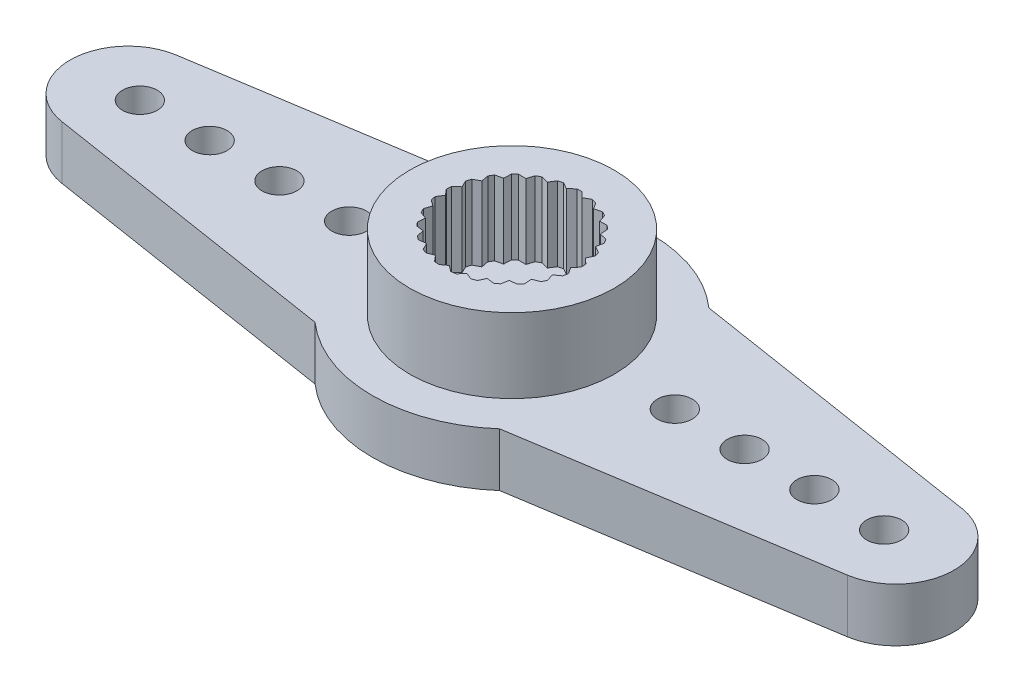
SolidWorks part; units mm, degrees
material "ABS"
ref_plane "Front Plane" through (0, 0, 0) normal (0, 0, 1) x (1, 0, 0)
ref_plane "Top Plane" through (0, 0, 0) normal (0, 1, 0) x (1, 0, 0)
ref_plane "Right Plane" through (0, 0, 0) normal (1, 0, 0) x (0, 0, -1)
sketch "Sketch2" plane through (0, 0, 0) normal (0, 1, 0) x (1, 0, 0)
  circle A0 centre (0, 0) radius 6
  circle A1 centre (0, 0) radius 1.5
  dimension "D1" = 12
  dimension "D2" = 3
extrude "Boss-Extrude1" add sketch "Sketch2" along normal mid plane 2.3
sketch "Sketch3" plane through (0, 1.15, 0) normal (0, 1, 0) x (1, 0, 0)
  line L0 (0, 0) -> (0, 2.9) construction
  line L3 (0, 0) -> (0.376, 2.9763) construction
  line L52 (0.1074, 2.898) -> (0.3384, 2.6787)
  line L53 (-0.1074, 2.898) -> (-0.3384, 2.6787)
  line L54 (0.8248, 2.7802) -> (0.9939, 2.5104)
  line L55 (0.6167, 2.8337) -> (0.3384, 2.6787)
  line L56 (1.4903, 2.4878) -> (1.587, 2.1843)
  line L57 (1.302, 2.5913) -> (0.9939, 2.5104)
  line L58 (2.0621, 2.039) -> (2.0804, 1.721)
  line L59 (1.9055, 2.1861) -> (1.587, 2.1843)
  line L60 (2.5044, 1.4621) -> (2.443, 1.1496)
  line L61 (2.3893, 1.6435) -> (2.0804, 1.721)
  line L62 (2.7894, 0.7934) -> (2.6522, 0.5059)
  line L63 (2.723, 0.9977) -> (2.443, 1.1496)
  line L64 (2.899, 0.0748) -> (2.6947, -0.1695)
  line L65 (2.8855, 0.2892) -> (2.6522, 0.5059)
  line L66 (2.8265, -0.6486) -> (2.5679, -0.8343)
  line L67 (2.8668, -0.4375) -> (2.6947, -0.1695)
  line L68 (2.5765, -1.3311) -> (2.2797, -1.4467)
  line L69 (2.6679, -1.1367) -> (2.5679, -0.8343)
  line L70 (2.1645, -1.93) -> (1.8483, -1.9682)
  line L71 (2.3014, -1.7645) -> (2.2797, -1.4467)
  line L72 (1.6165, -2.4077) -> (1.3007, -2.366)
  line L73 (1.7903, -2.2814) -> (1.8483, -1.9682)
  line L74 (0.967, -2.734) -> (0.6715, -2.6152)
  line L75 (1.1667, -2.655) -> (1.3007, -2.366)
  line L76 (0.2566, -2.8886) -> (0, -2.7)
  line L77 (0.4698, -2.8617) -> (0.6715, -2.6152)
  line L78 (-0.4698, -2.8617) -> (-0.6715, -2.6152)
  line L79 (-0.2566, -2.8886) -> (0, -2.7)
  line L80 (-1.1667, -2.655) -> (-1.3007, -2.366)
  line L81 (-0.967, -2.734) -> (-0.6715, -2.6152)
  line L82 (-1.7903, -2.2814) -> (-1.8483, -1.9682)
  line L83 (-1.6165, -2.4077) -> (-1.3007, -2.366)
  line L84 (-2.3014, -1.7645) -> (-2.2797, -1.4467)
  line L85 (-2.1645, -1.93) -> (-1.8483, -1.9682)
  line L86 (-2.6679, -1.1367) -> (-2.5679, -0.8343)
  line L87 (-2.5765, -1.3311) -> (-2.2797, -1.4467)
  line L88 (-2.8668, -0.4375) -> (-2.6947, -0.1695)
  line L89 (-2.8265, -0.6486) -> (-2.5679, -0.8343)
  line L90 (-2.8855, 0.2892) -> (-2.6522, 0.5059)
  line L91 (-2.899, 0.0748) -> (-2.6947, -0.1695)
  line L92 (-2.723, 0.9977) -> (-2.443, 1.1496)
  line L93 (-2.7894, 0.7934) -> (-2.6522, 0.5059)
  line L94 (-2.3893, 1.6435) -> (-2.0804, 1.721)
  line L95 (-2.5044, 1.4621) -> (-2.443, 1.1496)
  line L96 (-1.9055, 2.1861) -> (-1.587, 2.1843)
  line L97 (-2.0621, 2.039) -> (-2.0804, 1.721)
  line L98 (-1.302, 2.5913) -> (-0.9939, 2.5104)
  line L99 (-1.4903, 2.4878) -> (-1.587, 2.1843)
  line L100 (-0.6167, 2.8337) -> (-0.3384, 2.6787)
  line L101 (-0.8248, 2.7802) -> (-0.9939, 2.5104)
  line L102 (-2.533, 1.6075) -> (-2.3893, 1.6435) construction
  line L103 (-2.533, 1.6075) -> (-2.5044, 1.4621) construction
  line L104 (-2.8532, 0.9271) -> (-2.723, 0.9977) construction
  line L105 (-2.8532, 0.9271) -> (-2.7894, 0.7934) construction
  line L106 (-2.9941, 0.1884) -> (-2.8855, 0.2892) construction
  line L107 (-2.9941, 0.1884) -> (-2.899, 0.0748) construction
  line L108 (-2.9469, -0.5621) -> (-2.8668, -0.4375) construction
  line L109 (-2.9469, -0.5621) -> (-2.8265, -0.6486) construction
  line L110 (0, 3) -> (0.1074, 2.898) construction
  line L111 (0, 2.9) -> (0, 3) construction
  line L112 (0, 3) -> (-0.1074, 2.898) construction
  line L113 (-0.7461, 2.9057) -> (-0.6167, 2.8337) construction
  line L114 (-0.7461, 2.9057) -> (-0.8248, 2.7802) construction
  line L115 (-1.4453, 2.6289) -> (-1.302, 2.5913) construction
  line L116 (-1.4453, 2.6289) -> (-1.4903, 2.4878) construction
  line L117 (-2.0536, 2.1869) -> (-1.9055, 2.1861) construction
  line L118 (-2.0536, 2.1869) -> (-2.0621, 2.039) construction
  line L119 (-2.7145, -1.2773) -> (-2.6679, -1.1367) construction
  line L120 (-2.7145, -1.2773) -> (-2.5765, -1.3311) construction
  line L121 (-2.3115, -1.9123) -> (-2.3014, -1.7645) construction
  line L122 (-2.3115, -1.9123) -> (-2.1645, -1.93) construction
  line L123 (-1.7634, -2.4271) -> (-1.7903, -2.2814) construction
  line L124 (-1.7634, -2.4271) -> (-1.6165, -2.4077) construction
  line L125 (-1.1044, -2.7893) -> (-1.1667, -2.655) construction
  line L126 (-1.1044, -2.7893) -> (-0.967, -2.734) construction
  line L127 (-0.376, -2.9763) -> (-0.4698, -2.8617) construction
  line L128 (-0.376, -2.9763) -> (-0.2566, -2.8886) construction
  line L129 (0.376, -2.9763) -> (0.2566, -2.8886) construction
  line L130 (0.376, -2.9763) -> (0.4698, -2.8617) construction
  line L131 (1.1044, -2.7893) -> (0.967, -2.734) construction
  line L132 (1.1044, -2.7893) -> (1.1667, -2.655) construction
  line L133 (1.7634, -2.4271) -> (1.6165, -2.4077) construction
  line L134 (1.7634, -2.4271) -> (1.7903, -2.2814) construction
  line L135 (2.3115, -1.9123) -> (2.3014, -1.7645) construction
  line L136 (2.3115, -1.9123) -> (2.1645, -1.93) construction
  line L137 (2.7145, -1.2773) -> (2.6679, -1.1367) construction
  line L138 (2.7145, -1.2773) -> (2.5765, -1.3311) construction
  line L139 (2.9469, -0.5621) -> (2.8668, -0.4375) construction
  line L140 (2.9469, -0.5621) -> (2.8265, -0.6486) construction
  line L141 (2.9941, 0.1884) -> (2.8855, 0.2892) construction
  line L142 (2.9941, 0.1884) -> (2.899, 0.0748) construction
  line L143 (2.8532, 0.9271) -> (2.723, 0.9977) construction
  line L144 (2.8532, 0.9271) -> (2.7894, 0.7934) construction
  line L145 (2.533, 1.6075) -> (2.3893, 1.6435) construction
  line L146 (2.533, 1.6075) -> (2.5044, 1.4621) construction
  line L147 (2.0536, 2.1869) -> (1.9055, 2.1861) construction
  line L148 (2.0536, 2.1869) -> (2.0621, 2.039) construction
  line L149 (1.4453, 2.6289) -> (1.302, 2.5913) construction
  line L150 (1.4453, 2.6289) -> (1.4903, 2.4878) construction
  line L151 (0.7461, 2.9057) -> (0.6167, 2.8337) construction
  line L152 (0.7461, 2.9057) -> (0.8248, 2.7802) construction
  circle A0 centre (0, 0) radius 4.4
  circle A1 centre (0, 0) radius 3 construction
  circle A2 centre (0, 0) radius 2.7 construction
  arc A3 (-0.6167, 2.8337) -> (-0.8248, 2.7802) centre (0, 0) ccw
  arc A4 (-0.1074, 2.898) -> (-0.6167, 2.8337) centre (0, 0) ccw construction
  arc A5 (-0.8248, 2.7802) -> (-1.302, 2.5913) centre (0, 0) ccw construction
  arc A6 (-1.302, 2.5913) -> (-1.4903, 2.4878) centre (0, 0) ccw
  arc A7 (-1.4903, 2.4878) -> (-1.9055, 2.1861) centre (0, 0) ccw construction
  arc A8 (-1.9055, 2.1861) -> (-2.0621, 2.039) centre (0, 0) ccw
  arc A9 (-2.0621, 2.039) -> (-2.3893, 1.6435) centre (0, 0) ccw construction
  arc A10 (-2.3893, 1.6435) -> (-2.5044, 1.4621) centre (0, 0) ccw
  arc A11 (-2.5044, 1.4621) -> (-2.723, 0.9977) centre (0, 0) ccw construction
  arc A12 (-2.723, 0.9977) -> (-2.7894, 0.7934) centre (0, 0) ccw
  arc A13 (-2.7894, 0.7934) -> (-2.8855, 0.2892) centre (0, 0) ccw construction
  arc A14 (-2.8855, 0.2892) -> (-2.899, 0.0748) centre (0, 0) ccw
  arc A15 (-2.899, 0.0748) -> (-2.8668, -0.4375) centre (0, 0) ccw construction
  arc A16 (-2.8668, -0.4375) -> (-2.8265, -0.6486) centre (0, 0) ccw
  arc A17 (-2.8265, -0.6486) -> (-2.6679, -1.1367) centre (0, 0) ccw construction
  arc A18 (-2.6679, -1.1367) -> (-2.5765, -1.3311) centre (0, 0) ccw
  arc A19 (-2.5765, -1.3311) -> (-2.3014, -1.7645) centre (0, 0) ccw construction
  arc A20 (-2.3014, -1.7645) -> (-2.1645, -1.93) centre (0, 0) ccw
  arc A21 (-2.1645, -1.93) -> (-1.7903, -2.2814) centre (0, 0) ccw construction
  arc A22 (-1.7903, -2.2814) -> (-1.6165, -2.4077) centre (0, 0) ccw
  arc A23 (-1.6165, -2.4077) -> (-1.1667, -2.655) centre (0, 0) ccw construction
  arc A24 (-1.1667, -2.655) -> (-0.967, -2.734) centre (0, 0) ccw
  arc A25 (-0.967, -2.734) -> (-0.4698, -2.8617) centre (0, 0) ccw construction
  arc A26 (-0.4698, -2.8617) -> (-0.2566, -2.8886) centre (0, 0) ccw
  arc A27 (-0.2566, -2.8886) -> (0.2566, -2.8886) centre (0, 0) ccw construction
  arc A28 (0.2566, -2.8886) -> (0.4698, -2.8617) centre (0, 0) ccw
  arc A29 (0.4698, -2.8617) -> (0.967, -2.734) centre (0, 0) ccw construction
  arc A30 (0.967, -2.734) -> (1.1667, -2.655) centre (0, 0) ccw
  arc A31 (1.1667, -2.655) -> (1.6165, -2.4077) centre (0, 0) ccw construction
  arc A32 (1.6165, -2.4077) -> (1.7903, -2.2814) centre (0, 0) ccw
  arc A33 (1.7903, -2.2814) -> (2.1645, -1.93) centre (0, 0) ccw construction
  arc A34 (2.1645, -1.93) -> (2.3014, -1.7645) centre (0, 0) ccw
  arc A35 (2.3014, -1.7645) -> (2.5765, -1.3311) centre (0, 0) ccw construction
  arc A36 (2.5765, -1.3311) -> (2.6679, -1.1367) centre (0, 0) ccw
  arc A37 (2.6679, -1.1367) -> (2.8265, -0.6486) centre (0, 0) ccw construction
  arc A38 (2.8265, -0.6486) -> (2.8668, -0.4375) centre (0, 0) ccw
  arc A39 (2.8668, -0.4375) -> (2.899, 0.0748) centre (0, 0) ccw construction
  arc A40 (2.899, 0.0748) -> (2.8855, 0.2892) centre (0, 0) ccw
  arc A41 (2.8855, 0.2892) -> (2.7894, 0.7934) centre (0, 0) ccw construction
  arc A42 (2.7894, 0.7934) -> (2.723, 0.9977) centre (0, 0) ccw
  arc A43 (2.723, 0.9977) -> (2.5044, 1.4621) centre (0, 0) ccw construction
  arc A44 (2.5044, 1.4621) -> (2.3893, 1.6435) centre (0, 0) ccw
  arc A45 (2.3893, 1.6435) -> (2.0621, 2.039) centre (0, 0) ccw construction
  arc A46 (2.0621, 2.039) -> (1.9055, 2.1861) centre (0, 0) ccw
  arc A47 (1.9055, 2.1861) -> (1.4903, 2.4878) centre (0, 0) ccw construction
  arc A48 (1.4903, 2.4878) -> (1.302, 2.5913) centre (0, 0) ccw
  arc A49 (1.302, 2.5913) -> (0.8248, 2.7802) centre (0, 0) ccw construction
  arc A50 (0.8248, 2.7802) -> (0.6167, 2.8337) centre (0, 0) ccw
  arc A51 (0.3635, 2.8771) -> (0.1074, 2.898) centre (0, 0) ccw construction
  arc A52 (0.1074, 2.898) -> (-0.1074, 2.898) centre (0, 0) ccw
  arc A53 (0.6167, 2.8337) -> (0.3635, 2.8771) centre (0, 0) ccw construction
  point P84 (0, 0)
  dimension "D1" = 8.8
  dimension "D2" = 5.4
  dimension "D3" = 6
  dimension "D6" = 5.8
  dimension "D4" = 7.2
  dimension "D5" = 25
extrude "Boss-Extrude2" add sketch "Sketch3" along normal blind 3.2
sketch "Sketch4" plane through (0, 0, 0) normal (0, 1, 0) x (1, 0, 0)
  line L0 (0, 0) -> (16, 0) construction
  line L1 (3.9686, 4.5) -> (16.8881, 2.4697)
  line L2 (3.9686, -4.5) -> (16.8881, -2.4697)
  line L3 (16, 0) -> (13, 0) construction
  circle A0 centre (0, 0) radius 6 construction
  arc A1 (3.9686, -4.5) -> (3.9686, 4.5) centre (0, 0) ccw
  arc A2 (16.8881, 2.4697) -> (16.8881, -2.4697) centre (16.5, 0) cw
  circle A3 centre (16, 0) radius 0.75
  circle A4 centre (13, 0) radius 0.75
  circle A5 centre (10, 0) radius 0.75
  circle A6 centre (7, 0) radius 0.75
  dimension "D3" = 2.5
  dimension "D5" = 1.5
  dimension "D2" = 9
  dimension "D7" = 3
  dimension "D4" = 0.5
  dimension "D1" = 16
  dimension "D6" = 4
extrude "Boss-Extrude3" add sketch "Sketch4" along normal mid plane 2.3
pattern_circular "CirPattern1" count 2 over 360 about axis through (0, 0, 0) along (0, 1, 0) of "Boss-Extrude3"
sketch "Sketch5" plane through (0, 0, 0) normal (0, 1, 0) x (1, 0, 0)
  line L0 (3, 7) -> (-3, 7) construction
  circle A0 centre (0, 0) radius 10
  circle A1 centre (0, 7) radius 0.75
  circle A2 centre (-3, 7) radius 0.75
  circle A3 centre (3, 7) radius 0.75
  circle A4 centre (7, 3) radius 0.75
  circle A5 centre (7, 0) radius 0.75
  circle A6 centre (7, -3) radius 0.75
  circle A7 centre (3, -7) radius 0.75
  circle A8 centre (0, -7) radius 0.75
  circle A9 centre (-3, -7) radius 0.75
  circle A10 centre (-7, -3) radius 0.75
  circle A11 centre (-7, 0) radius 0.75
  circle A12 centre (-7, 3) radius 0.75
  circle A13 centre (0, 0) radius 1.5 construction
  circle A14 centre (0, 0) radius 1.5
  point P8 (0, 7)
  point P31 (0, 0)
  dimension "D1" = 1.5
  dimension "D3" = 2.25
  dimension "D4" = 6
  dimension "D2" = 7
  dimension "D5" = 4
extrude "Boss-Extrude4" [suppressed] add sketch "Sketch5" along normal mid plane 2.3
sketch "Sketch6" plane through (0, 1.15, 0) normal (0, 1, 0) x (1, 0, 0)
  line L0 (-16.8881, 2.4697) -> (-3.9686, 4.5)
  line L1 (-16.8881, -2.4697) -> (-3.9686, -4.5)
  line L2 (3.9686, 4.5) -> (16.8881, 2.4697)
  line L3 (16.8881, -2.4697) -> (3.9686, -4.5)
  arc A0 (-16.8881, 2.4697) -> (-16.8881, -2.4697) centre (-16.5, 0) ccw
  arc A1 (-3.9686, 4.5) -> (3.9686, 4.5) centre (0, 0) cw
  arc A2 (-3.9686, -4.5) -> (3.9686, -4.5) centre (0, 0) ccw
  arc A3 (16.8881, -2.4697) -> (16.8881, 2.4697) centre (16.5, 0) ccw
equation "\"N_hole\"= 4"
equation "\"N_horn\"= 2"
equation "\"D6@Sketch4\"=\"N_hole\""
equation "\"D1@CirPattern1\"=\"N_horn\""
equation "\"D1@Sketch4\"=(\"N_hole\" - 1) *3 +7"
